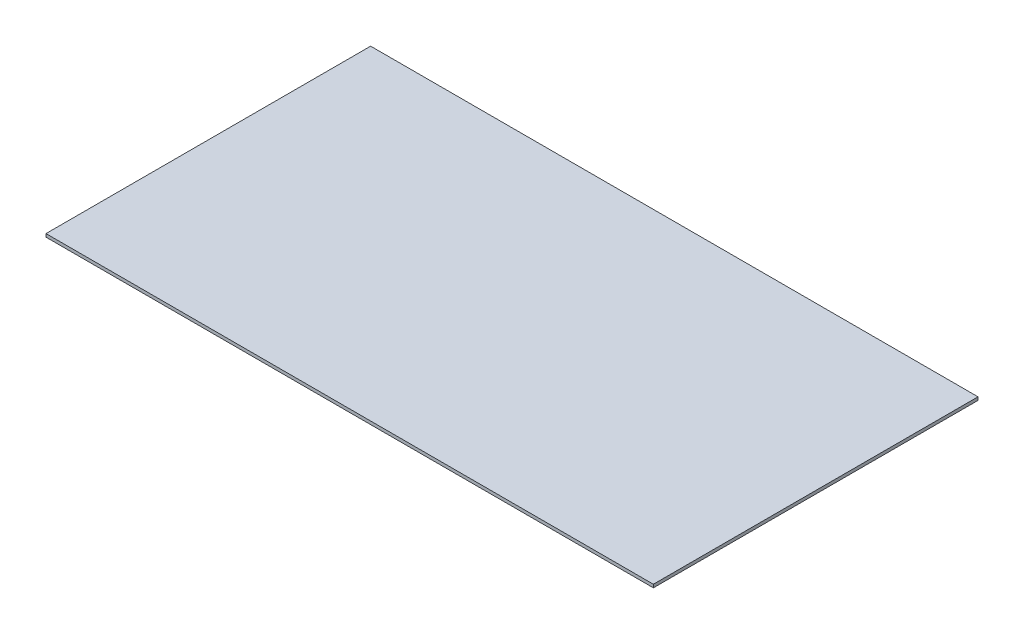
SolidWorks part; units mm, degrees
ref_plane "前视基准面" through (0, 0, 0) normal (0, 0, 1) x (1, 0, 0)
ref_plane "上视基准面" through (0, 0, 0) normal (0, 1, 0) x (1, 0, 0)
ref_plane "右视基准面" through (0, 0, 0) normal (1, 0, 0) x (0, 0, -1)
sketch "草图1" plane through (0, 0, 0) normal (0, 1, 0) x (1, 0, 0)
  line L1 (-290, 155) -> (290, 155)
  line L2 (-290, 155) -> (-290, -155)
  line L3 (-290, -155) -> (290, -155)
  line L4 (290, 155) -> (290, -155)
  line L5 (-290, 155) -> (290, -155) construction
  line L6 (-290, -155) -> (290, 155) construction
  point P0 (0, 0)
extrude "凸台-拉伸1" add sketch "草图1" along normal blind 3
